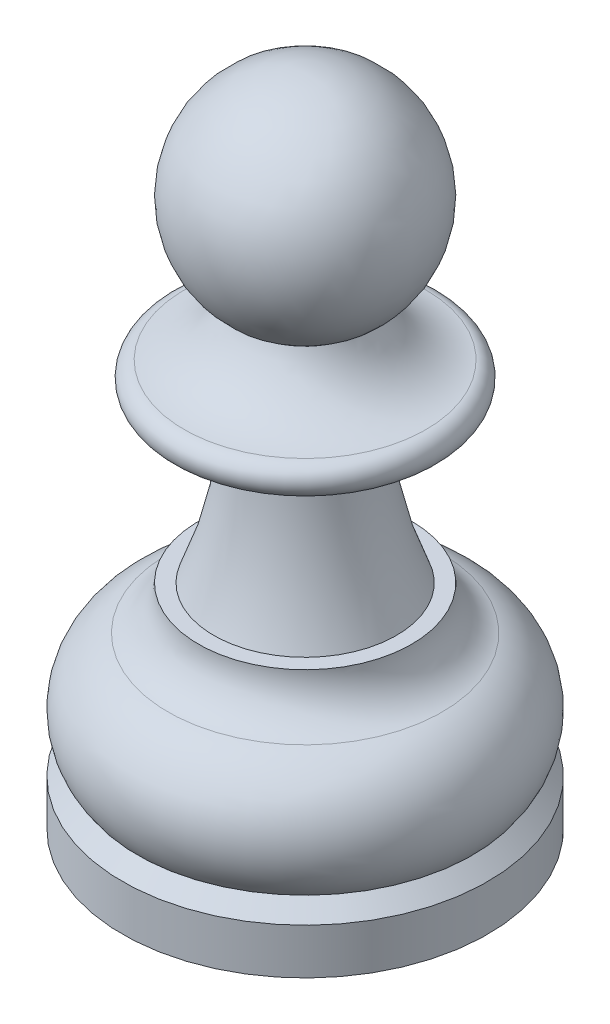
SolidWorks part; units mm, degrees
ref_plane "Front Plane" through (0, 0, 0) normal (0, 0, 1) x (1, 0, 0)
ref_plane "Top Plane" through (0, 0, 0) normal (0, 1, 0) x (1, 0, 0)
ref_plane "Right Plane" through (0, 0, 0) normal (1, 0, 0) x (0, 0, -1)
sketch "Sketch1" plane through (0, 0, 0) normal (0, 0, 1) x (1, 0, 0)
  line L0 (0, 0) -> (0, 43)
  line L1 (0, 0) -> (12, 0)
  line L2 (12, 0) -> (12, 3)
  line L3 (12, 3) -> (11, 4)
  line L4 (4, 24) -> (8, 24.7053)
  line L5 (4, 24) -> (-1000, 24) construction
  line L6 (6, 14) -> (7, 14)
  arc A0 (11, 4) -> (9, 11.1407) centre (7.4341, 6.8516) ccw
  arc A1 (3.6056, 30) -> (0, 43) centre (0, 36) ccw
  arc A2 (8, 24.7053) -> (7.9437, 26.6832) centre (7.8264, 25.6901) ccw
  arc A3 (3.6056, 30) -> (7.9437, 26.6832) centre (8.5722, 32.0007) ccw
  arc A4 (7, 14) -> (9, 11.1407) centre (10.044, 14) ccw
  arc A6 (4, 24) -> (6, 14) centre (30, 24) ccw
  point P9 (3.6056, 30)
  point P11 (4, 24)
  point P12 (8, 24.7053)
  point P25 (8.6529, 9.1575)
  dimension "D6" = 1
  dimension "D7" = 7
  dimension "D13" = 2
  dimension "D14" = 14
  dimension "D15" = 6
  dimension "D16" = 5.3545
  dimension "D1" = 43
  dimension "D2" = 12
  dimension "D3" = 3
  dimension "D4" = 1
  dimension "D5" = 45
  dimension "D8" = 30
  dimension "D9" = 4
  dimension "D10" = 24
  dimension "D11" = 8
  dimension "D12" = 10
  dimension "D17" = 9
revolve "Revolve2" add sketch "Sketch1" angle 360 about L0
